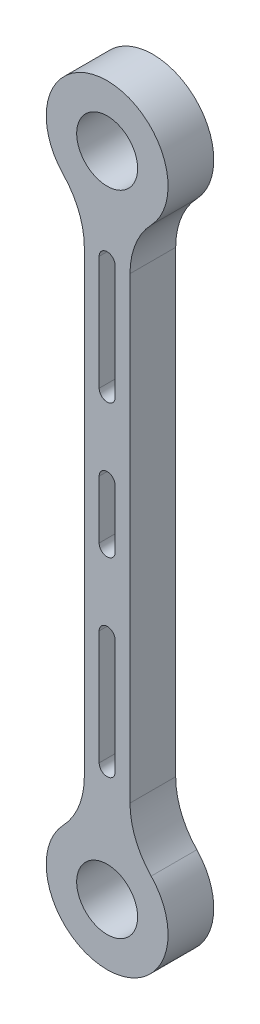
SolidWorks part; units mm, degrees
material "Thornel Mat VMA"
ref_plane "前视基准面" through (0, 0, 0) normal (0, 0, 1) x (1, 0, 0)
ref_plane "上视基准面" through (0, 0, 0) normal (0, 1, 0) x (1, 0, 0)
ref_plane "右视基准面" through (0, 0, 0) normal (1, 0, 0) x (0, 0, -1)
sketch "草图1" plane through (0, 0, 0) normal (0, 0, 1) x (1, 0, 0)
  line L0 (0, 0) -> (0, -50000) construction
  line L1 (-3, -7.4162) -> (-3, -77.6838)
  line L2 (3, -7.4162) -> (3, -77.6838)
  line L3 (0, -12.5) -> (0, -27.5) construction
  line L4 (1.05, -12.5) -> (1.05, -27.5)
  line L5 (-1.05, -12.5) -> (-1.05, -27.5)
  line L6 (0, -37.5) -> (0, -45.1) construction
  line L7 (1.05, -37.5) -> (1.05, -45.1)
  line L8 (-1.05, -37.5) -> (-1.05, -45.1)
  line L9 (0, -55.1) -> (0, -70.1) construction
  line L10 (1.05, -55.1) -> (1.05, -70.1)
  line L11 (-1.05, -55.1) -> (-1.05, -70.1)
  circle A0 centre (0, 0) radius 4
  circle A1 centre (0, -85.1) radius 4
  circle A2 centre (0, -85.1) radius 8
  circle A3 centre (0, 0) radius 8
  arc A4 (1.05, -12.5) -> (-1.05, -12.5) centre (0, -12.5) ccw
  arc A5 (-1.05, -27.5) -> (1.05, -27.5) centre (0, -27.5) ccw
  arc A6 (1.05, -37.5) -> (-1.05, -37.5) centre (0, -37.5) ccw
  arc A7 (-1.05, -45.1) -> (1.05, -45.1) centre (0, -45.1) ccw
  arc A8 (1.05, -55.1) -> (-1.05, -55.1) centre (0, -55.1) ccw
  arc A9 (-1.05, -70.1) -> (1.05, -70.1) centre (0, -70.1) ccw
  point P14 (0, -20)
  point P19 (0, -41.3)
  point P29 (0, -62.6)
  dimension "D2" = 8
  dimension "D3" = 4
  dimension "D4" = 4
  dimension "D1" = 85.1
  dimension "D5" = 3
  dimension "D6" = 2.1
  dimension "D7" = 2.1
  dimension "D8" = 15
  dimension "D9" = 10
  dimension "D10" = 20
  dimension "D11" = 10
  dimension "D12" = 2.1
  dimension "D13" = 15
  dimension "D14" = 15
extrude "凸台-拉伸1" add sketch "草图1" along normal blind 6 contours A3 L1 A2 L2 A9 L11 A8 L10 A7 L8 A6 L7 A5 L5 A4 L4 | A3 A0 | A2 A1
fillet "圆角1" radius 10 4 edges at (3, -77.6838, 3) (-3, -77.6838, 3) (3, -7.4162, 3) (-3, -7.4162, 3)
